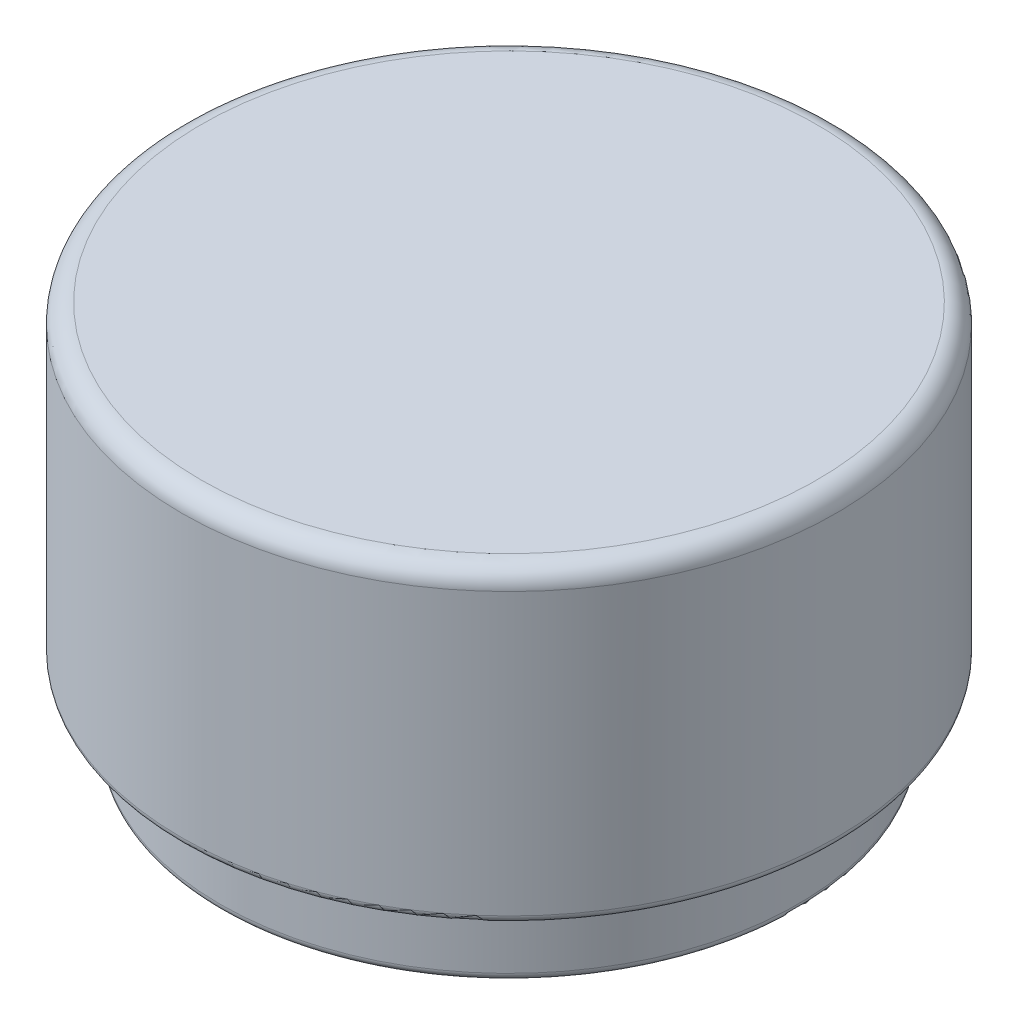
SolidWorks part; units mm, degrees
ref_plane "Front Plane" through (0, 0, 0) normal (0, 0, 1) x (1, 0, 0)
ref_plane "Top Plane" through (0, 0, 0) normal (0, 1, 0) x (1, 0, 0)
ref_plane "Right Plane" through (0, 0, 0) normal (1, 0, 0) x (0, 0, -1)
sketch "Sketch1" plane through (0, 0, 0) normal (1, 0, 0) x (0, 0, -1)
  line L0 (0, 0) -> (0, -10) construction
  line L1 (0, 0) -> (-8.5, 0)
  line L2 (0, -0.5) -> (-8, -0.5)
  line L3 (-7.5, -8) -> (-8.5, -8)
  line L4 (-8.5, 0) -> (-8.5, -8)
  line L5 (-8, -0.5) -> (-8, -7.5)
  line L6 (-7.5, -8) -> (-7.5, -10)
  line L7 (-7.5, -10) -> (0, -10) construction
  line L8 (-7, -7.5) -> (-8, -7.5)
  line L9 (-7, -7.5) -> (-7, -10)
  line L10 (0, 0) -> (0, -0.5)
  line L11 (-7, -10) -> (-7.5, -10)
  dimension "D1" = 8
  dimension "D2" = 8.5
  dimension "D3" = 10
  dimension "D4" = 7.5
  dimension "D5" = 0.5
revolve "Revolve1" add sketch "Sketch1" angle 360 about L0
fillet "Fillet1" radius 0.5 1 edges at (0, 0, 8.5)
fillet "Fillet2" radius 0.2 5 edges at (0, -0.5, 8) (0, -7.5, 7) (0, -10, 7) (0, -10, 7.5) (0, -8, 8.5)
